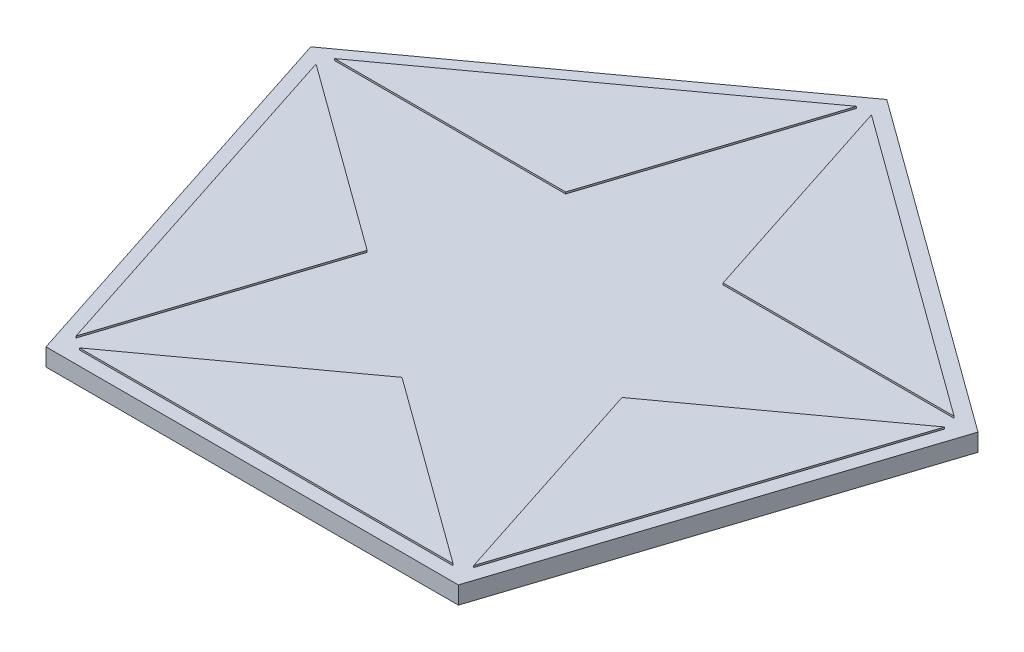
SolidWorks part; units mm, degrees
ref_plane "Front Plane" through (0, 0, 0) normal (0, 0, 1) x (1, 0, 0)
ref_plane "Top Plane" through (0, 0, 0) normal (0, 1, 0) x (1, 0, 0)
ref_plane "Right Plane" through (0, 0, 0) normal (1, 0, 0) x (0, 0, -1)
sketch "Sketch1" plane through (0, 0, 0) normal (0, 1, 0) x (1, 0, 0)
  line L0 (-0.2103, 9.3528) -> (-8.83, 3.0902)
  line L1 (5.8779, -8.0902) -> (9.5106, 3.0902)
  line L2 (9.5106, 3.0902) -> (0, 10)
  line L3 (0, 10) -> (-9.5106, 3.0902)
  line L4 (-9.5106, 3.0902) -> (-5.8779, -8.0902)
  line L5 (-5.8779, -8.0902) -> (5.8779, -8.0902)
  line L6 (-8.96, 2.6902) -> (-5.6676, -7.443)
  line L7 (-5.3273, -7.6902) -> (5.3273, -7.6902)
  line L8 (5.6676, -7.443) -> (8.96, 2.6902)
  line L9 (8.83, 3.0902) -> (0.2103, 9.3528)
  line L10 (0, 9.5056) -> (-9.0403, 2.9374) construction
  line L11 (9.0403, 2.9374) -> (0, 9.5056) construction
  line L12 (-8.96, 2.6902) -> (-3.6327, -1.1803) construction
  line L13 (5.5872, -7.6902) -> (9.0403, 2.9374) construction
  line L14 (-5.6676, -7.443) -> (-3.6327, -1.1803) construction
  line L15 (0.2103, 9.3528) -> (2.2451, 3.0902) construction
  line L16 (-0.2103, 9.3528) -> (-2.2451, 3.0902)
  line L17 (8.96, 2.6902) -> (3.6327, -1.1803)
  line L18 (5.3273, -7.6902) -> (-0.0508, -3.7828)
  line L19 (-8.83, 3.0902) -> (-2.2451, 3.0902)
  line L20 (8.83, 3.0902) -> (2.2451, 3.0902)
  line L21 (2.2451, 3.0902) -> (0.2103, 9.3528)
  line L22 (5.6676, -7.443) -> (3.6012, -1.0833)
  line L23 (-9.0403, 2.9374) -> (-5.5872, -7.6902) construction
  line L24 (3.6012, -1.0833) -> (5.6676, -7.443) construction
  line L25 (-0.0508, -3.7828) -> (5.3273, -7.6902) construction
  line L26 (-3.6327, -1.1803) -> (-8.96, 2.6902)
  line L27 (-5.5872, -7.6902) -> (5.5872, -7.6902) construction
  line L28 (0, -3.8197) -> (-5.3273, -7.6902)
  line L29 (-2.2451, 3.0902) -> (-0.2103, 9.3528) construction
  line L30 (-3.6327, -1.1803) -> (-5.6676, -7.443)
  circle A0 centre (0, 0) radius 10 construction
  dimension "D1" = 20
  dimension "D2" = 0.4
extrude "Boss-Extrude1" add sketch "Sketch1" along normal mid plane 0.5
sketch "Sketch2" plane through (0, 0.25, 0) normal (0, 1, 0) x (1, 0, 0)
  line L0 (2.2451, 3.0902) -> (0.2103, 9.3528) construction
  line L1 (8.83, 3.0902) -> (0.2103, 9.3528) construction
  line L2 (8.83, 3.0902) -> (2.2451, 3.0902) construction
  line L3 (5.6676, -7.443) -> (8.96, 2.6902) construction
  line L4 (8.96, 2.6902) -> (3.6327, -1.1803) construction
  line L5 (-9.5106, 3.0902) -> (-5.8779, -8.0902)
  line L6 (-5.8779, -8.0902) -> (5.8779, -8.0902)
  line L7 (5.8779, -8.0902) -> (9.5106, 3.0902)
  line L8 (9.5106, 3.0902) -> (0, 10)
  line L9 (0, 10) -> (-9.5106, 3.0902)
  line L10 (-9.5106, 3.0902) -> (-5.8779, -8.0902)
  line L11 (-5.8779, -8.0902) -> (5.8779, -8.0902)
  line L12 (5.8779, -8.0902) -> (9.5106, 3.0902)
  line L13 (9.5106, 3.0902) -> (0, 10)
  line L14 (0, 10) -> (-9.5106, 3.0902)
  line L15 (5.6676, -7.443) -> (3.6327, -1.1803) construction
  line L16 (-5.3273, -7.6902) -> (5.3273, -7.6902) construction
  line L17 (5.3273, -7.6902) -> (0, -3.8197) construction
  line L18 (0, -3.8197) -> (-5.3273, -7.6902) construction
  line L19 (-3.6327, -1.1803) -> (-5.6676, -7.443) construction
  line L20 (-8.96, 2.6902) -> (-5.6676, -7.443) construction
  line L21 (-3.6327, -1.1803) -> (-8.96, 2.6902) construction
  line L22 (-0.2103, 9.3528) -> (-8.83, 3.0902) construction
  line L23 (-0.2103, 9.3528) -> (-2.2451, 3.0902) construction
  line L24 (-8.83, 3.0902) -> (-2.2451, 3.0902) construction
  line L25 (2.2451, 3.0902) -> (0.2103, 9.3528)
  line L26 (8.83, 3.0902) -> (0.2103, 9.3528)
  line L27 (8.83, 3.0902) -> (2.2451, 3.0902)
  line L28 (5.6676, -7.443) -> (8.96, 2.6902)
  line L29 (8.96, 2.6902) -> (3.6327, -1.1803)
  line L30 (5.6676, -7.443) -> (3.6327, -1.1803)
  line L31 (-5.3273, -7.6902) -> (5.3273, -7.6902)
  line L32 (5.3273, -7.6902) -> (0, -3.8197)
  line L33 (0, -3.8197) -> (-5.3273, -7.6902)
  line L34 (-3.6327, -1.1803) -> (-5.6676, -7.443)
  line L35 (-8.96, 2.6902) -> (-5.6676, -7.443)
  line L36 (-3.6327, -1.1803) -> (-8.96, 2.6902)
  line L37 (-0.2103, 9.3528) -> (-8.83, 3.0902)
  line L38 (-0.2103, 9.3528) -> (-2.2451, 3.0902)
  line L39 (-8.83, 3.0902) -> (-2.2451, 3.0902)
  line L40 (-0.2103, 9.3528) -> (-8.83, 3.0902)
  line L41 (-8.83, 3.0902) -> (-2.2451, 3.0902)
  line L42 (-0.2103, 9.3528) -> (-2.2451, 3.0902)
  line L43 (8.83, 3.0902) -> (2.2451, 3.0902)
  line L44 (2.2451, 3.0902) -> (0.2103, 9.3528)
  line L45 (8.83, 3.0902) -> (0.2103, 9.3528)
  line L46 (8.96, 2.6902) -> (3.6327, -1.1803)
  line L47 (5.6676, -7.443) -> (3.6327, -1.1803)
  line L48 (5.6676, -7.443) -> (8.96, 2.6902)
  line L49 (0, -3.8197) -> (-5.3273, -7.6902)
  line L50 (-5.3273, -7.6902) -> (5.3273, -7.6902)
  line L51 (5.3273, -7.6902) -> (0, -3.8197)
  line L52 (-3.6327, -1.1803) -> (-5.6676, -7.443)
  line L53 (-8.96, 2.6902) -> (-5.6676, -7.443)
  line L54 (-3.6327, -1.1803) -> (-8.96, 2.6902)
  line M11 (-5.3273, -7.6902) -> (0, -3.8197)
  line M12 (0, -3.8197) -> (5.3273, -7.6902)
  line M13 (5.3273, -7.6902) -> (-5.3273, -7.6902)
  line M14 (-2.2451, 3.0902) -> (-8.83, 3.0902)
  line M15 (-8.83, 3.0902) -> (-0.2103, 9.3528)
  line M16 (-0.2103, 9.3528) -> (-2.2451, 3.0902)
  line M22 (8.83, 3.0902) -> (2.2451, 3.0902)
  line M23 (2.2451, 3.0902) -> (0.2103, 9.3528)
  line M24 (0.2103, 9.3528) -> (8.83, 3.0902)
  line M25 (8.96, 2.6902) -> (5.6676, -7.443)
  line M26 (5.6676, -7.443) -> (3.6327, -1.1803)
  line M27 (3.6327, -1.1803) -> (8.96, 2.6902)
  line M28 (-8.96, 2.6902) -> (-3.6327, -1.1803)
  line M29 (-3.6327, -1.1803) -> (-5.6676, -7.443)
  line M30 (-5.6676, -7.443) -> (-8.96, 2.6902)
  dimension "D1" = 0
  dimension "D2" = 0
extrude "Boss-Extrude2" add sketch "Sketch2" along normal mid plane 0.1 contours M14 M16 M15 | M28 M30 M29 | M11 M13 M12 | M25 M27 M26 | M22 M24 M23
